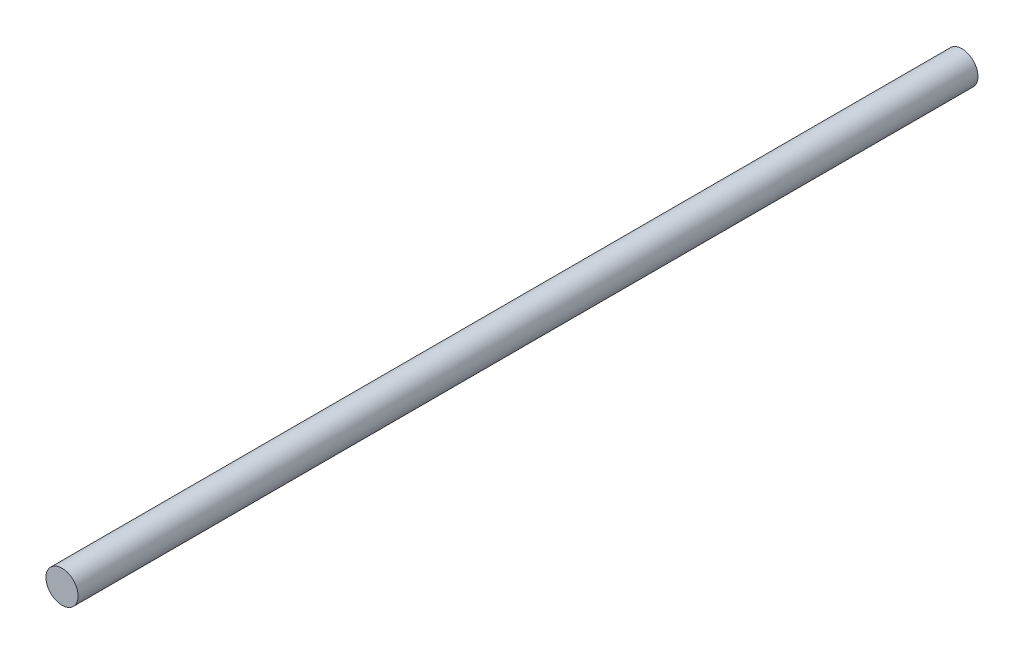
SolidWorks part; units mm, degrees
ref_plane "Front Plane" through (0, 0, 0) normal (0, 0, 1) x (1, 0, 0)
ref_plane "Top Plane" through (0, 0, 0) normal (0, 1, 0) x (1, 0, 0)
ref_plane "Right Plane" through (0, 0, 0) normal (1, 0, 0) x (0, 0, -1)
sketch "Sketch1" plane through (0, 0, 0) normal (0, 0, 1) x (1, 0, 0)
  circle A0 centre (-4.2266, 0) radius 2.5
extrude "Boss-Extrude1" add sketch "Sketch1" along normal blind 140
